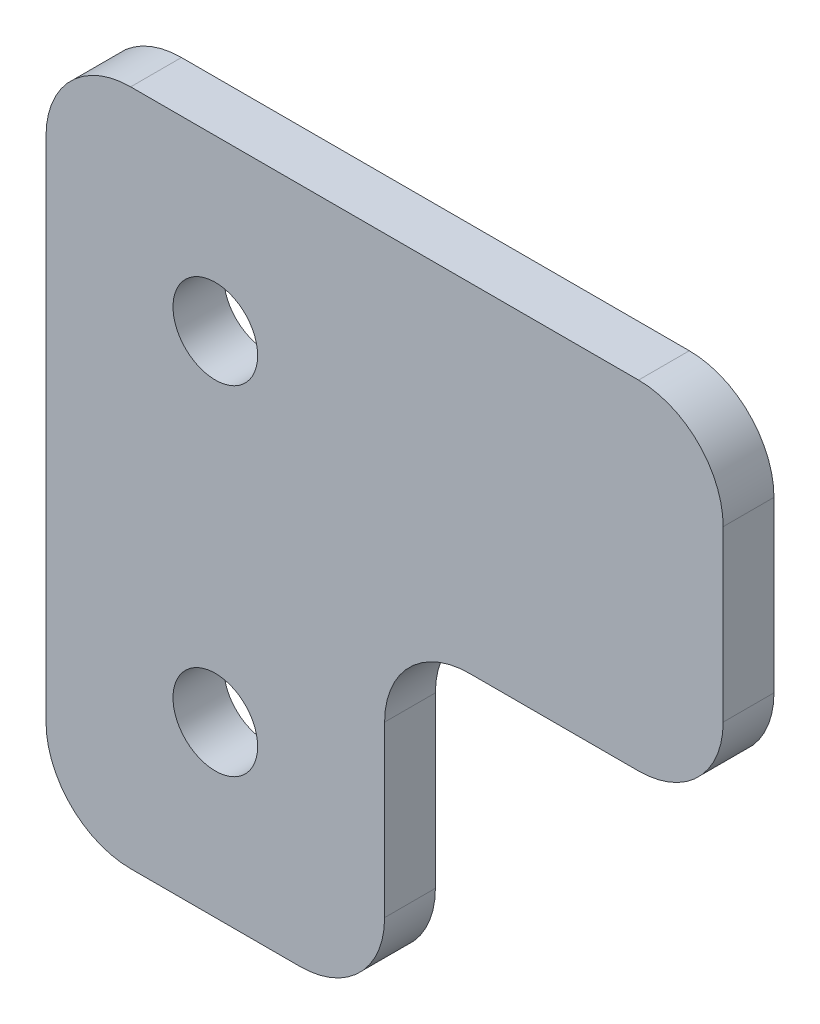
SolidWorks part; units mm, degrees
ref_plane "正面" through (0, 0, 0) normal (0, 0, 1) x (1, 0, 0)
ref_plane "平面" through (0, 0, 0) normal (0, 1, 0) x (1, 0, 0)
ref_plane "右側面" through (0, 0, 0) normal (1, 0, 0) x (0, 0, -1)
sketch "ｽｹｯﾁ2" plane through (0, 0, 0) normal (0, 0, 1) x (1, 0, 0)
  line L0 (0, 0) -> (0, 20) construction
  line L1 (10, 30) -> (30, 30)
  line L2 (10, 30) -> (-10, 30)
  line L3 (10, 30) -> (10, -10) construction
  line L4 (10, -10) -> (-10, -10)
  line L5 (-10, 30) -> (-10, -10)
  line L6 (10, 30) -> (-10, -10) construction
  line L7 (10, -10) -> (-10, 30) construction
  line L8 (30, 30) -> (30, 10)
  line L9 (30, 10) -> (10, 10)
  line L10 (10, 10) -> (10, -10)
  circle A0 centre (0, 0) radius 2.5
  circle A1 centre (0, 20) radius 2.5
  point P3 (0, 10)
  dimension "D1" = 20
  dimension "D2" = 5
  dimension "D3" = 20
  dimension "D4" = 40
  dimension "D5" = 20
extrude "ﾎﾞｽ - 押し出し1" add sketch "ｽｹｯﾁ2" along normal blind 3
fillet "ﾌｨﾚｯﾄ1" radius 5 6 edges at (30, 30, 1.5) (30, 10, 1.5) (-10, -10, 1.5) (10, -10, 1.5) (10, 10, 1.5) (-10, 30, 1.5)
